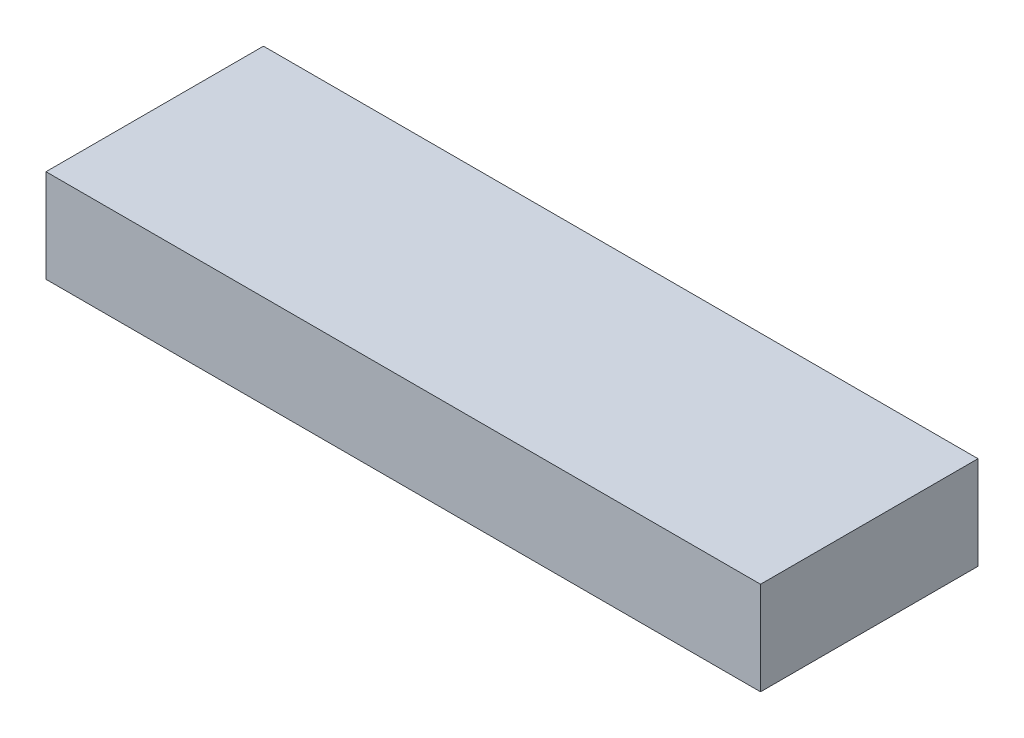
SolidWorks part; units mm, degrees
material "Pine"
ref_plane "Front Plane" through (0, 0, 0) normal (0, 0, 1) x (1, 0, 0)
ref_plane "Top Plane" through (0, 0, 0) normal (0, 1, 0) x (1, 0, 0)
ref_plane "Right Plane" through (0, 0, 0) normal (1, 0, 0) x (0, 0, -1)
sketch "Sketch1" plane through (0, 0, 0) normal (1, 0, 0) x (0, 0, -1)
  line L1 (0, 0) -> (88.9, 0)
  line L2 (0, 0) -> (0, 38.1)
  line L3 (0, 38.1) -> (88.9, 38.1)
  line L4 (88.9, 0) -> (88.9, 38.1)
  dimension "D1" = 88.9
  dimension "D2" = 38.1
extrude "Boss-Extrude1" add sketch "Sketch1" along normal blind 292.1
